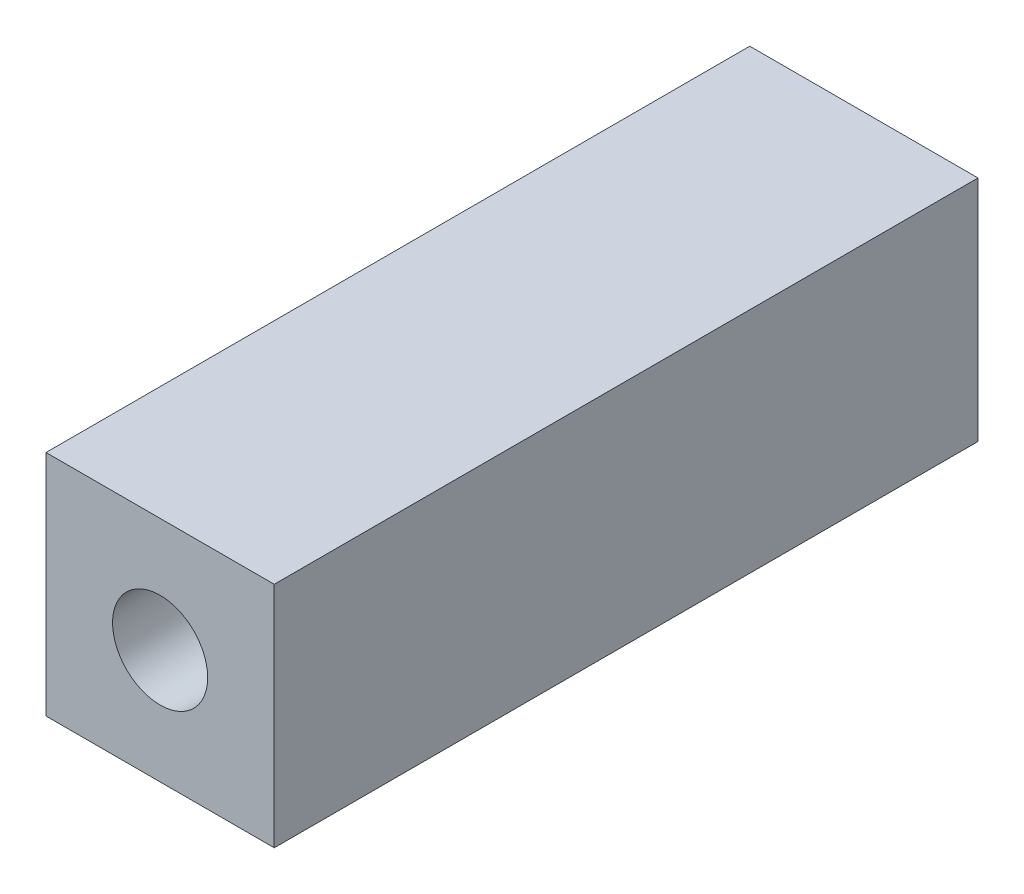
SolidWorks part; units mm, degrees
material "ABS PC"
ref_plane "Front Plane" through (0, 0, 0) normal (0, 0, 1) x (1, 0, 0)
ref_plane "Top Plane" through (0, 0, 0) normal (0, 1, 0) x (1, 0, 0)
ref_plane "Right Plane" through (0, 0, 0) normal (1, 0, 0) x (0, 0, -1)
sketch "Sketch1" plane through (0, 0, 0) normal (0, 0, 1) x (1, 0, 0)
  line L1 (-6, 6) -> (6, 6)
  line L2 (-6, 6) -> (-6, -6)
  line L3 (-6, -6) -> (6, -6)
  line L4 (6, 6) -> (6, -6)
  line L5 (-6, 6) -> (6, -6) construction
  line L6 (-6, -6) -> (6, 6) construction
  point P0 (0, 0)
  dimension "D1" = 12
  dimension "D2" = 12
extrude "Boss-Extrude1" add sketch "Sketch1" along normal blind 37
sketch "Sketch2" plane through (0, 0, 0) normal (0, 0, -1) x (-1, 0, 0)
  line L1 (4, 4) -> (-4, 4)
  line L2 (4, 4) -> (4, -4)
  line L3 (4, -4) -> (-4, -4)
  line L4 (-4, 4) -> (-4, -4)
  line L5 (4, 4) -> (-4, -4) construction
  line L6 (4, -4) -> (-4, 4) construction
  point P0 (0, 0)
  dimension "D1" = 8
  dimension "D2" = 8
extrude "Cut-Extrude1" cut sketch "Sketch2" against normal blind 30
sketch "Sketch3" plane through (0, 0, 37) normal (0, 0, 1) x (1, 0, 0)
  circle A0 centre (0, 0) radius 2.5
  dimension "D1" = 5
extrude "Cut-Extrude2" cut sketch "Sketch3" against normal up to next
